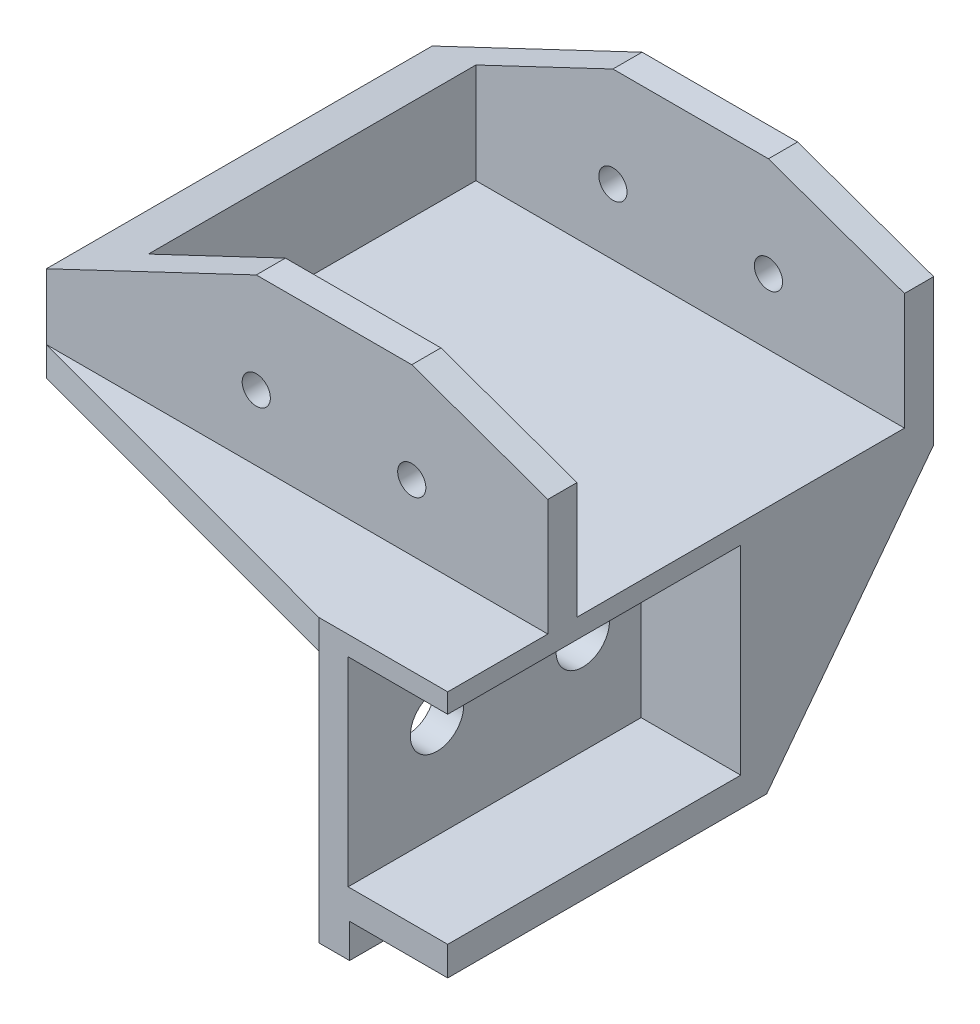
SolidWorks part; units mm, degrees
ref_plane "前视基准面" through (0, 0, 0) normal (0, 0, 1) x (1, 0, 0)
ref_plane "上视基准面" through (0, 0, 0) normal (0, 1, 0) x (1, 0, 0)
ref_plane "右视基准面" through (0, 0, 0) normal (1, 0, 0) x (0, 0, -1)
sketch "草图1" plane through (0, 0, 0) normal (0, 0, 1) x (1, 0, 0)
  line L0 (0, 0) -> (-103.2, 0)
  line L1 (-103.2, 0) -> (-103.2, 20)
  line L2 (-103.2, 20) -> (0, 20)
  line L3 (0, 20) -> (0, 0)
  dimension "D1" = 103.2
  dimension "D2" = 20
extrude "凸台-拉伸1" add sketch "草图1" along normal blind 39.7
sketch "草图2" plane through (0, 20, 0) normal (0, 1, 0) x (1, 0, 0)
  line L0 (-51.6, 0) -> (-51.6, -39.7) construction
  line L2 (-99.2, -19.85) -> (-72.6862, -19.85) construction
  line L5 (-95.7, -3) -> (-7.5, -3)
  line L6 (-95.7, -3) -> (-95.7, -36.7)
  line L7 (-95.7, -36.7) -> (-7.5, -36.7)
  line L8 (-7.5, -3) -> (-7.5, -36.7)
  dimension "D1" = 88.2
  dimension "D2" = 33.7
extrude "切除-拉伸1" cut sketch "草图2" against normal offset from surface (17 mm away) 3 up to face at (-51.6, 0, 19.85)
sketch "草图3" plane through (0, 0, 0) normal (0, -1, 0) x (1, 0, 0)
  line L6 (-51.6, 39.7) -> (-51.6, -13.7739) construction
  line L11 (-103.2, 0) -> (0, 0) construction
  line L12 (-64.85, 0) -> (-38.35, 0)
  line L15 (-64.85, 0) -> (-64.85, 50)
  line L16 (-64.85, 50) -> (-38.35, 50)
  line L17 (-38.35, 50) -> (-38.35, 0)
  point P11 (-51.6, 0)
  dimension "D1" = 50
  dimension "D2" = 13.25
extrude "凸台-拉伸2" add sketch "草图3" along normal blind 29 from offset 3 offset against normal yes
sketch "草图21" plane through (0, 0, 50) normal (0, 0, 1) x (1, 0, 0)
  line L0 (-7.5, 3) -> (-95.7, 3) construction
  line L1 (-7.5, 3) -> (-95.7, 3) construction
  line L2 (-98.033, -9.25) -> (-9.0097, -9.25) construction
  line L3 (-51.6, -26) -> (-51.6, 30.6239) construction
  line L4 (-61.85, 1) -> (-41.35, 1)
  line L5 (-61.85, 1) -> (-61.85, -19.5)
  line L6 (-61.85, -19.5) -> (-41.35, -19.5)
  line L7 (-41.35, 1) -> (-41.35, -19.5)
  dimension "D1" = 12.25
  dimension "D2" = 20.5
  dimension "D3" = 20.5
extrude "切除-拉伸11" cut sketch "草图21" against normal offset from surface (30.15 mm away) 19.85 up to face at (-51.6, -1.5, 0)
sketch "草图22" plane through (0, -26, 0) normal (0, -1, 0) x (1, 0, 0)
  line L1 (-61.7, 50) -> (-41.5, 50)
  line L2 (-41.5, 50) -> (-41.5, 0)
  line L3 (-64.85, 0) -> (-38.35, 0) construction
  line L4 (-41.5, 0) -> (-61.7, 0)
  line L5 (-61.7, 0) -> (-61.7, 50)
  line L6 (-38.35, 50) -> (-64.85, 50) construction
  dimension "D1" = 0
extrude "切除-拉伸12" cut sketch "草图22" against normal offset from surface (3.5 mm away) 3 up to face at (-51.6, -19.5, 34.925)
sketch "草图24" plane through (-38.35, 0, 0) normal (1, 0, 0) x (0, 0, -1)
  line L0 (0, 0) -> (0, -26)
  line L1 (0, -26) -> (-19.85, -26)
  line L2 (0, -26) -> (-50, -26) construction
  line L3 (-19.85, -26) -> (0, 0)
  line L4 (-19.85, -19.5) -> (-19.85, 1) construction
  line L5 (-19.85, -19.5) -> (-19.85, 1) construction
extrude "切除-拉伸14" cut sketch "草图24" against normal through all
sketch "草图25" plane through (0, 0, 0) normal (0, -1, 0) x (1, 0, 0)
  line L0 (-38.35, 39.7) -> (-38.35, 50)
  line L1 (-38.35, 50) -> (0, 39.7)
  line L2 (-51.6, 50) -> (-51.6, 41.294) construction
  line L4 (-38.35, 39.7) -> (0, 39.7)
  line L5 (-64.85, 39.7) -> (-103.2, 39.7)
  line L6 (-64.85, 50) -> (-103.2, 39.7)
  line L7 (-64.85, 39.7) -> (-64.85, 50)
extrude "凸台-拉伸4" add sketch "草图25" against normal up to surface (3 mm away) up to face at (-51.6, 3, 44.85)
hole_wizard "M2.5 间隙孔1" positions "草图26" profile "草图27" hole size "M2.5" standard "ISO" end condition through all
sketch "草图26" plane through (0, 0, 0) normal (0, 0, -1) x (-1, 0, 0)
  line L0 (-2.4764, 3) -> (110.5641, 3) construction
  line L2 (38.35, 0) -> (0, 0) construction
  line L3 (51.6, 0) -> (51.6, 22.298) construction
  point P8 (37.6, 9.75)
  point P10 (21.6, 9.75)
  point P23 (65.6, 9.75)
  point P24 (81.6, 9.75)
  dimension "D1" = 3
  dimension "D2" = 14
  dimension "D3" = 16
  dimension "D4" = 6.75
  dimension "D5" = 6.75
sketch "草图27" plane through (-81.6, 9.75, 0) normal (1, 0, 0) x (0, 1, 0)
  line L0 (0, 0) -> (0, 50)
  line L1 (0, 50) -> (1.45, 50)
  line L2 (1.45, 50) -> (1.45, 0.025)
  line L3 (1.45, 0.025) -> (1.475, 0)
  line L5 (1.475, 0) -> (0, 0)
  line L6 (-1.45, 0.025) -> (-1.475, 0) construction
  line L11 (0, -6.35) -> (0, 107.95) construction
  dimension "通孔孔直径" = 2.9
  dimension "通孔孔深度" = 50
  dimension "近端锥形沉头孔直径" = 2.95
  dimension "近端锥形沉头孔角度" = 90
hole_wizard "M5 间隙孔2" positions "草图34" profile "草图33" hole size "M5" standard "ISO" end condition through all
sketch "草图34" plane through (-38.35, 0, 0) normal (1, 0, 0) x (0, 0, -1)
  line L2 (-43.9538, -9.25) -> (-19.6706, -9.25) construction
  line L5 (-19.85, 0.85) -> (-19.85, -19.35) construction
  line L7 (-19.85, 1) -> (-50, 1) construction
  point P10 (-25.85, -9.25)
  point P21 (-40.85, -9.25)
  dimension "D1" = 6
  dimension "D2" = 15
sketch "草图33" plane through (-38.35, -9.25, 40.85) normal (0, 1, 0) x (0, 0, -1)
  line L0 (0, 0) -> (0, 64.85)
  line L1 (0, 64.85) -> (2.75, 64.85)
  line L2 (2.75, 64.85) -> (2.75, 0.025)
  line L3 (2.75, 0.025) -> (2.775, 0)
  line L5 (2.775, 0) -> (0, 0)
  line L6 (-2.75, 0.025) -> (-2.775, 0) construction
  line L11 (0, -6.35) -> (0, 107.95) construction
  dimension "通孔孔直径" = 5.5
  dimension "通孔孔深度" = 64.85
  dimension "近端锥形沉头孔直径" = 5.55
  dimension "近端锥形沉头孔角度" = 90
sketch "草图35" plane through (0, 0, 0) normal (0, 0, -1) x (-1, 0, 0)
  line L0 (21.6, 9.75) -> (37.6, 9.75) construction
  line L1 (21.6, 9.75) -> (21.6, 21.6918) construction
  line L2 (37.6, 9.75) -> (37.6, 21.6918) construction
  line L3 (0, 9.75) -> (21.6, 20)
  line L4 (0, 0) -> (0, 20) construction
  line L5 (21.6, 20) -> (0, 20)
  line L6 (0, 20) -> (0, 9.75)
  line L7 (0, 20) -> (103.2, 20) construction
  line L8 (51.6, 0) -> (51.6, 24.4852) construction
  line L10 (37.6, 20) -> (51.6, 15)
  line L11 (51.6, 15) -> (51.6, 20)
  line L12 (65.6, 20) -> (37.6, 20)
  line L13 (81.6, 20) -> (103.2, 20)
  line L14 (103.2, 9.75) -> (81.6, 20)
  line L15 (103.2, 20) -> (103.2, 9.75)
  line L16 (65.6, 20) -> (51.6, 15)
  line M17 (103.2, 0) -> (103.2, 20)
  line M18 (103.2, 20) -> (0, 20)
  dimension "D1" = 5
extrude "切除-拉伸19" cut sketch "草图35" against normal through all contours L14 M17 M18 | L6 L3 L5 | L16 L12 L10
ref_plane "基准面1" through (-51.6, 0, 0) normal (-1, 0, 0) x (0, 0, 1)
sketch "草图36" plane through (-51.6, 0, 0) normal (-1, 0, 0) x (0, 0, 1)
  line L1 (0, 20) -> (50, 20)
  line L2 (0, 20) -> (0, -26)
  line L3 (0, -26) -> (50, -26)
  line L4 (50, 20) -> (50, -26)
extrude "切除-拉伸20" cut sketch "草图36" against normal up to surface (51.6 mm away) up to face at (0, 4.5, 23.82)
